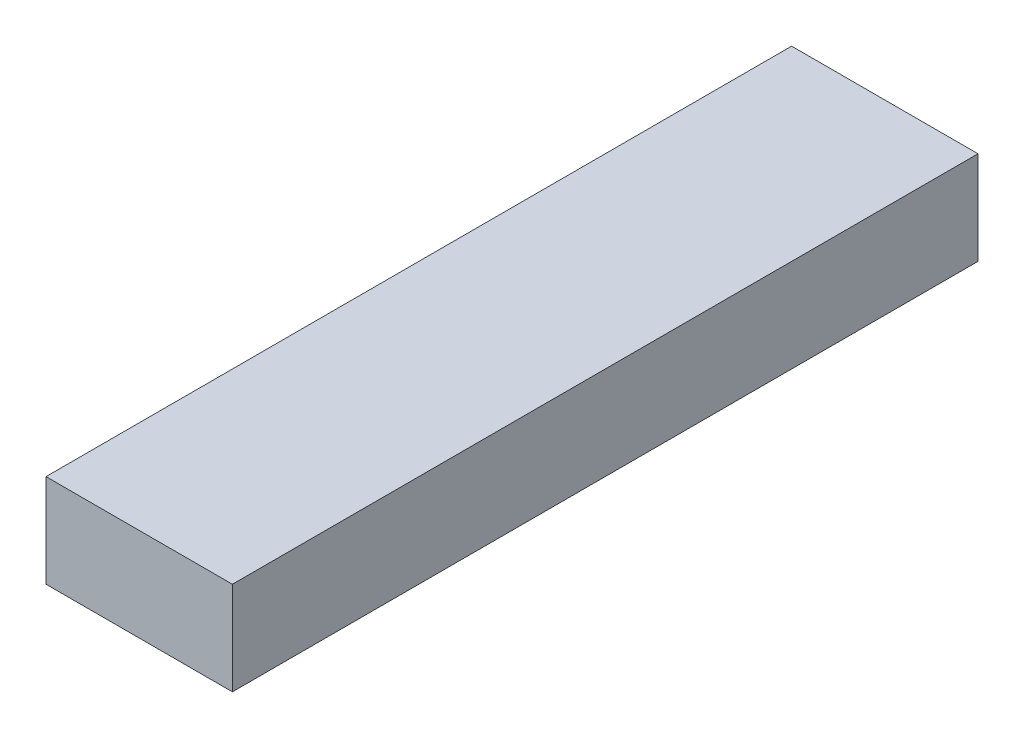
SolidWorks part; units mm, degrees
ref_plane "前视基准面" through (0, 0, 0) normal (0, 0, 1) x (1, 0, 0)
ref_plane "上视基准面" through (0, 0, 0) normal (0, 1, 0) x (1, 0, 0)
ref_plane "右视基准面" through (0, 0, 0) normal (1, 0, 0) x (0, 0, -1)
other "Configuration Table"
sketch "Profile1" plane through (0, 0, 0) normal (0, 0, 1) x (1, 0, 0)
  line L1 (-5, -2.5) -> (5, -2.5)
  line L2 (-5, -2.5) -> (-5, 2.5)
  line L3 (-5, 2.5) -> (5, 2.5)
  line L4 (5, -2.5) -> (5, 2.5)
sketch "Path1" plane through (0, 0, 0) normal (1, 0, 0) x (0, 0, -1)
  line L0 (0, 0) -> (-40, 0)
sweep "modern_sweep_merge_false" add profiles "Profile1" path "Path1"
